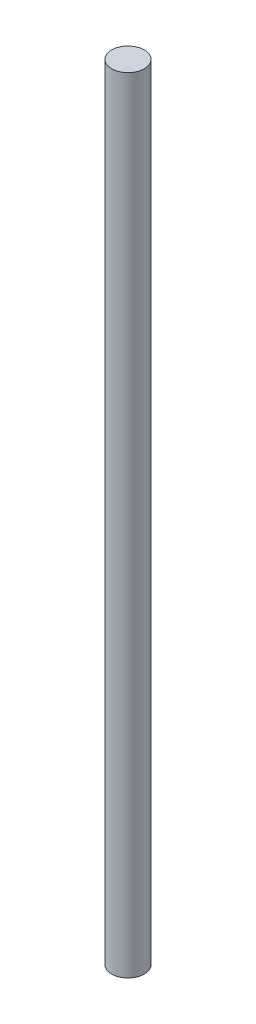
SolidWorks part; units mm, degrees
ref_plane "Спереди" through (0, 0, 0) normal (0, 0, 1) x (1, 0, 0)
ref_plane "Сверху" through (0, 0, 0) normal (0, 1, 0) x (1, 0, 0)
ref_plane "Справа" through (0, 0, 0) normal (1, 0, 0) x (0, 0, -1)
sketch "Эскиз1" plane through (0, 0, 0) normal (0, 1, 0) x (1, 0, 0)
  circle A0 centre (0, 0) radius 5
  dimension "D1" = 10
extrude "Вытянуть1" add sketch "Эскиз1" along normal blind 240
